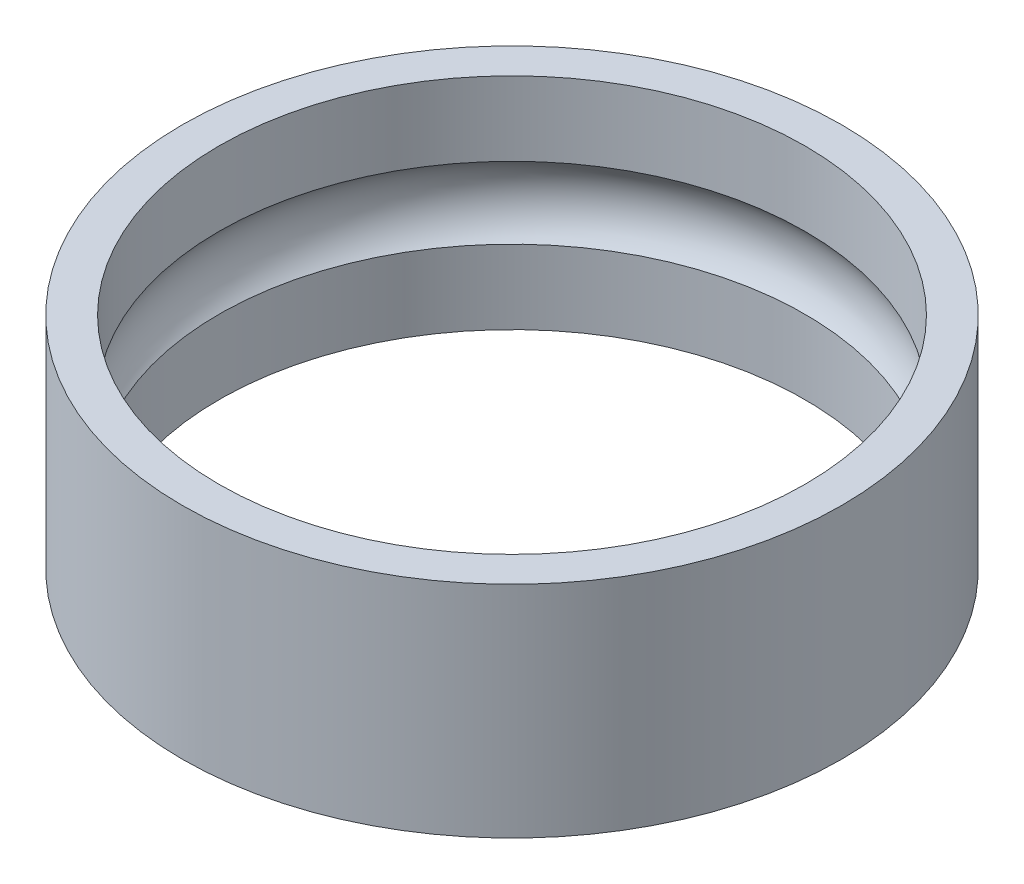
SolidWorks part; units mm, degrees
material "Chrome Stainless Steel"
ref_plane "Front Plane" through (0, 0, 0) normal (0, 0, 1) x (1, 0, 0)
ref_plane "Top Plane" through (0, 0, 0) normal (0, 1, 0) x (1, 0, 0)
ref_plane "Right Plane" through (0, 0, 0) normal (1, 0, 0) x (0, 0, -1)
sketch "Diameter Profile Sketch" plane through (0, 0, 0) normal (0, 1, 0) x (1, 0, 0)
  circle A0 centre (0, 0) radius 4
  circle A1 centre (0, 0) radius 4.5
  dimension "InnerDia" = 8
  dimension "Thickness" = 0.5
extrude "Diameter Profile" add sketch "Diameter Profile Sketch" along normal mid plane 3
sketch "Bearing Path Profile Sketch" plane through (0, 0, 0) normal (0, 0, 1) x (1, 0, 0)
  line L1 (0, 0) -> (3.5, 0) construction
  circle A0 centre (3.5, 0) radius 0.7
  point P7 (4, 1.5)
  dimension "BallDia" = 1.4
  dimension "YDim" = 0.5
  dimension "RefRadius" = 3.5
revolve "Bearing Path Profile" cut sketch "Bearing Path Profile Sketch" angle 360 about axis through (0, 1.5, 0) along (0, -1, 0)
